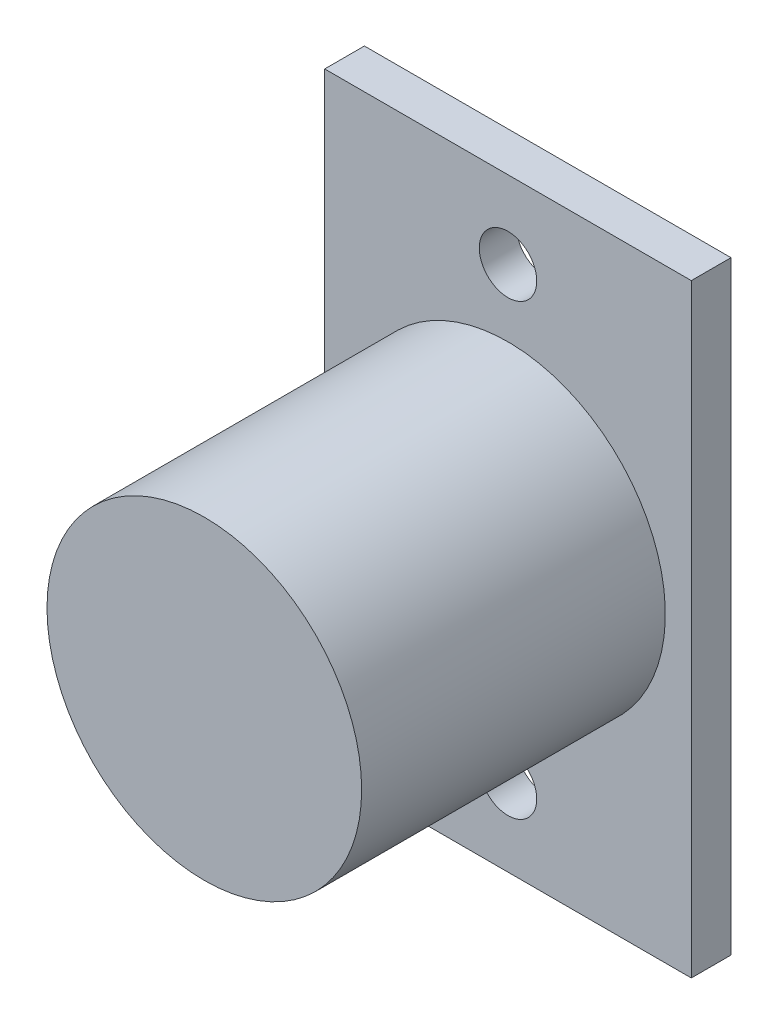
SolidWorks part; units mm, degrees
ref_plane "Front Plane" through (0, 0, 0) normal (0, 0, 1) x (1, 0, 0)
ref_plane "Top Plane" through (0, 0, 0) normal (0, 1, 0) x (1, 0, 0)
ref_plane "Right Plane" through (0, 0, 0) normal (1, 0, 0) x (0, 0, -1)
sketch "Sketch1" plane through (0, 0, 0) normal (0, 0, 1) x (1, 0, 0)
  line L1 (0, 0) -> (22.0472, 0)
  line L2 (0, 0) -> (0, 36.322)
  line L3 (0, 36.322) -> (22.0472, 36.322)
  line L4 (22.0472, 0) -> (22.0472, 36.322)
  dimension "D1" = 36.322
  dimension "D2" = 22.0472
extrude "Boss-Extrude1" add sketch "Sketch1" along normal blind 2.3876
sketch "Sketch2" plane through (0, 0, 0) normal (0, 0, -1) x (-1, 0, 0)
  line L0 (-11.0236, 36.322) -> (-11.0236, 0) construction
  line L1 (-22.0472, 36.322) -> (0, 36.322) construction
  line L2 (0, 0) -> (-22.0472, 0) construction
  line L3 (-22.0472, 18.161) -> (0, 18.161) construction
  line L4 (-22.0472, 0) -> (-22.0472, 36.322) construction
  line L5 (0, 36.322) -> (0, 0) construction
  circle A0 centre (-11.0236, 31.6484) radius 1.7272
  circle A1 centre (-11.0236, 4.6736) radius 1.7272
  circle A2 centre (-11.0236, 18.161) radius 8.89
  dimension "D1" = 3.4544
  dimension "D2" = 26.9748
  dimension "D3" = 17.78
extrude "Cut-Extrude1" cut sketch "Sketch2" against normal up to next
sketch "Sketch3" plane through (0, 0, 2.3876) normal (0, 0, 1) x (1, 0, 0)
  circle A0 centre (11.0236, 18.161) radius 9.4615
  dimension "D1" = 18.923
extrude "Boss-Extrude2" add sketch "Sketch3" along normal blind 18.2626
chamfer "Chamfer1" distance 1.1303 angle 8 2 edges at (9.2964, 31.6484, 0) (12.7508, 4.6736, 0)
